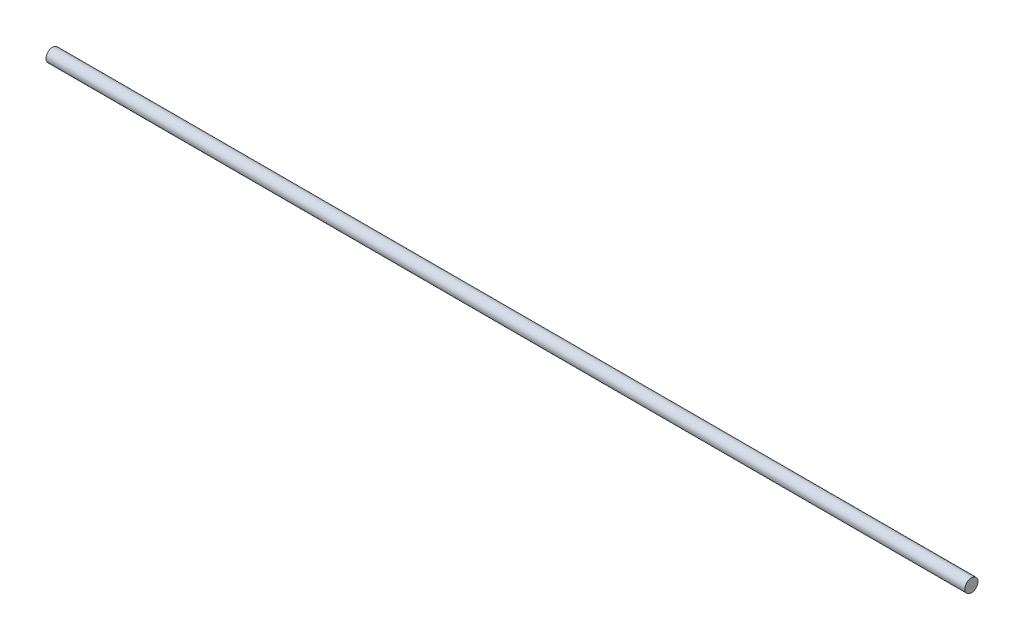
SolidWorks part; units mm, degrees
ref_plane "Front Plane" through (0, 0, 0) normal (0, 0, 1) x (1, 0, 0)
ref_plane "Top Plane" through (0, 0, 0) normal (0, 1, 0) x (1, 0, 0)
ref_plane "Right Plane" through (0, 0, 0) normal (1, 0, 0) x (0, 0, -1)
sketch "Sketch1" plane through (0, 0, 0) normal (0, 0, 1) x (1, 0, 0)
  line L0 (-37.5, 0) -> (37.5, 0) construction
  line L1 (37.5, 2.5) -> (37.5, -2.5) construction
  line L2 (-37.5, 2.5) -> (-37.5, -2.5) construction
  point P6 (34.7, -2.5)
  dimension "D1" = 2.8
  dimension "Thread Diameter" = 5
  dimension "Length" = 75
sketch "Sketch2" plane through (0, 0, 0) normal (1, 0, 0) x (0, 0, -1)
  circle A0 centre (0, 0) radius 2.5
extrude "Boss-Extrude1" add sketch "Sketch2" against normal blind 350
